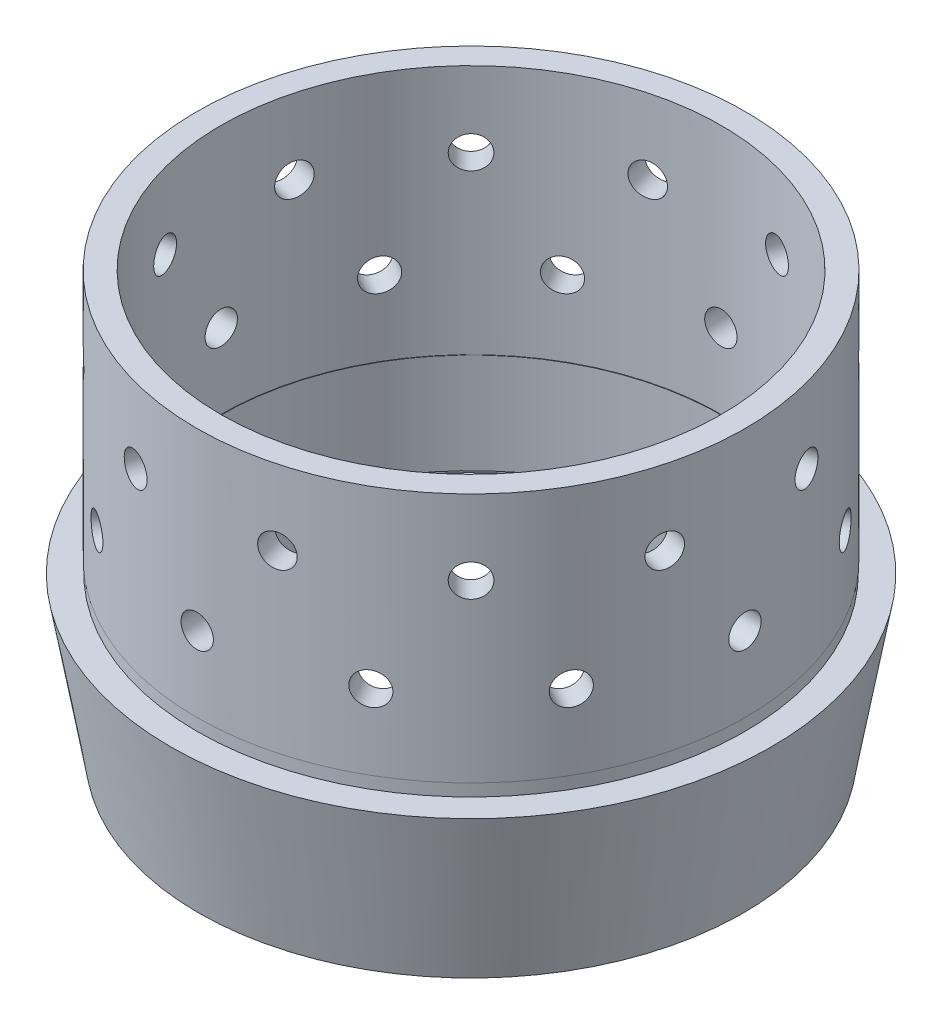
SolidWorks part; units mm, degrees
ref_plane "Front Plane" through (0, 0, 0) normal (0, 0, 1) x (1, 0, 0)
ref_plane "Top Plane" through (0, 0, 0) normal (0, 1, 0) x (1, 0, 0)
ref_plane "Right Plane" through (0, 0, 0) normal (1, 0, 0) x (0, 0, -1)
sketch "Sketch1" plane through (0, 0, 0) normal (0, 1, 0) x (1, 0, 0)
  circle A0 centre (0, 0) radius 69.596
  circle A1 centre (0, 0) radius 63.5
  dimension "D1" = 139.192
  dimension "D2" = 127
extrude "Boss-Extrude1" add sketch "Sketch1" along normal blind 63.5
ref_plane "Plane1" through (0, 0, 69.596) normal (0, 0, 1) x (1, 0, 0)
sketch "Sketch2" plane through (0, 0, 69.596) normal (0, 0, 1) x (1, 0, 0)
  circle A0 centre (0, 19.05) radius 4.1021
  dimension "D1" = 8.2042
  dimension "D2" = 19.05
extrude "Cut-Extrude1" cut sketch "Sketch2" against normal up to next
pattern_circular "CirPattern1" count 12 over 360 about axis through (0, 63.5, 0) along (0, -1, 0) of "Cut-Extrude1"
ref_plane "Plane2" through (-18.0128, 0, 67.2246) normal (-0.2588, 0, 0.9659) x (0, -1, 0)
sketch "Sketch3" plane through (-18.0128, 0, 67.2246) normal (-0.2588, 0, 0.9659) x (0, -1, 0)
  line L0 (0, -69.596) -> (0, 69.596) construction
  circle A0 centre (-44.45, 0) radius 4.1021
  dimension "D2" = 8.2042
  dimension "D1" = 44.45
extrude "Cut-Extrude2" cut sketch "Sketch3" against normal up to next
pattern_circular "CirPattern2" count 12 over 360 about axis through (0, 63.5, 0) along (0, -1, 0) of "Cut-Extrude2"
sketch "Sketch4" plane through (0, 0, 0) normal (-0.4067, 0, 0.9135) x (0.9135, 0, 0.4067)
  line L0 (-63.373, 0) -> (-69.469, 0)
  line L1 (-69.596, 0) -> (69.596, 0) construction
  line L2 (-69.85, 0) -> (69.85, 0) construction
  line L3 (-76.2, -3.175) -> (-69.146, -43.18)
  line L5 (-63.373, -28.1686) -> (-63.373, -31.7491)
  line L6 (-63.5, 0) -> (63.5, 0) construction
  line L7 (-63.373, 0) -> (-63.373, -25.4)
  line L11 (-63.373, -31.7491) -> (-63.373, -43.18)
  line L12 (-63.373, -43.18) -> (-69.146, -43.18)
  line L14 (-66.675, -25.4) -> (-66.675, -28.1686)
  line L15 (-66.675, -28.1686) -> (-63.373, -28.1686)
  line L16 (-66.675, -25.4) -> (-63.373, -25.4)
  line L17 (-69.469, 0) -> (-69.469, -3.175)
  line L18 (-69.469, -3.175) -> (-76.2, -3.175)
  line L19 (66.802, -25.4) -> (-66.802, -25.4) construction
  dimension "D1" = 17.78
  dimension "D2" = 76.2
  dimension "D3" = 17.78
  dimension "D4" = 63.373
  dimension "D5" = 80
  dimension "D6" = 2.7686
  dimension "D7" = 66.675
  dimension "D8" = 3.175
  dimension "D9" = 6.096
ref_axis "Axis1" through (0, 63.5, 0) along (0, -1, 0)
revolve "Revolve1" add sketch "Sketch4" angle 360 about axis through (0, 63.5, 0) along (0, -1, 0)
